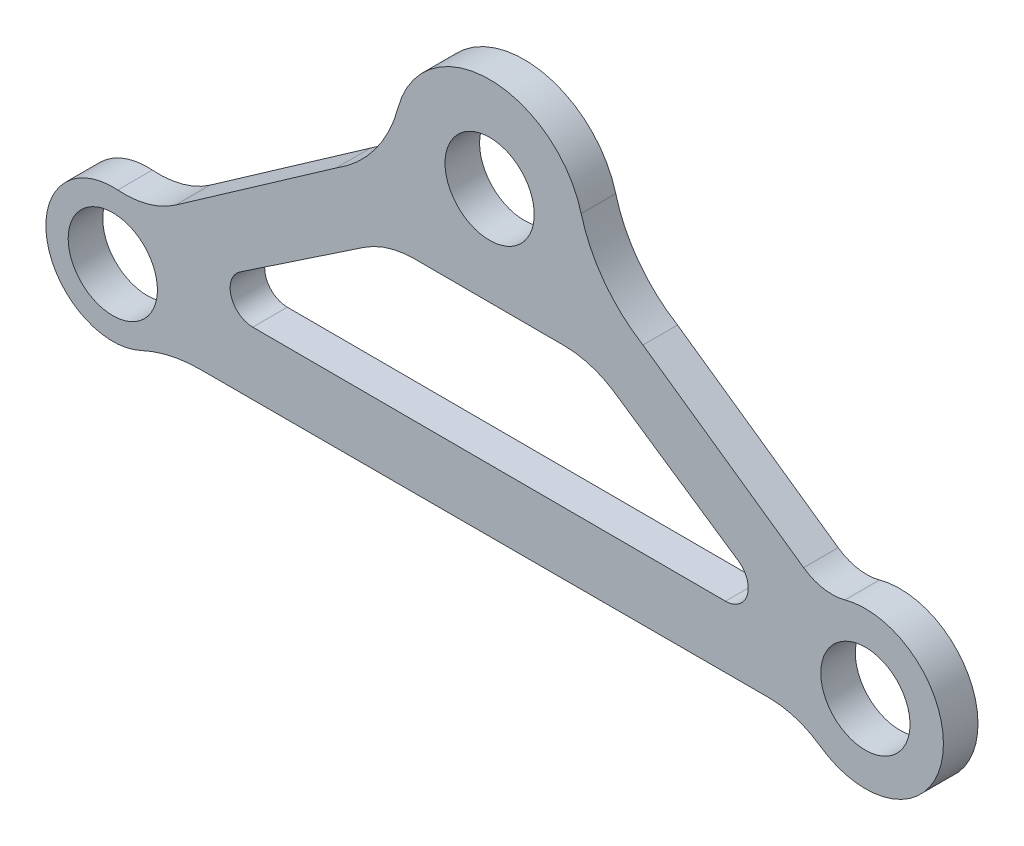
SolidWorks part; units mm, degrees
ref_plane "Front Plane" through (0, 0, 0) normal (0, 0, 1) x (1, 0, 0)
ref_plane "Top Plane" through (0, 0, 0) normal (0, 1, 0) x (1, 0, 0)
ref_plane "Right Plane" through (0, 0, 0) normal (1, 0, 0) x (0, 0, -1)
sketch "Sketch1" plane through (0, 0, 0) normal (0, 0, 1) x (1, 0, 0)
  line L0 (13.3736, -17.6685) -> (-13.446, -17.6134)
  line L1 (-22.5576, -20.3787) -> (-44.7444, -35.2777)
  line L2 (-42.4832, -42.7284) -> (42.3075, -42.9023)
  line L3 (44.5992, -35.461) -> (22.4738, -20.4711)
  line L4 (56.3265, -30.6845) -> (27.5, -10.5)
  line L6 (-27.5, -10.5) -> (-56.3265, -30.6845)
  line L8 (-51.8851, -54) -> (50.0933, -54)
  line L11 (-67.5934, -45.5) -> (67.4066, -45.5) construction
  circle A0 centre (67.4066, -45.5) radius 8
  circle A1 centre (0, 0) radius 8
  circle A2 centre (-67.5934, -45.5) radius 8
  arc A3 (-13.446, -17.6134) -> (-22.5576, -20.3787) centre (-13.4794, -33.8974) ccw
  arc A4 (-44.7444, -35.2777) -> (-42.4832, -42.7284) centre (-42.4748, -38.6574) ccw
  arc A5 (42.3075, -42.9023) -> (44.5992, -35.461) centre (42.3159, -38.8314) ccw
  arc A6 (22.4738, -20.4711) -> (13.3736, -17.6685) centre (13.3402, -33.9525) ccw
  arc A7 (59.327, -56.9333) -> (63.7525, -31.9853) centre (67.4066, -45.5) ccw
  arc A8 (56.3265, -30.6845) -> (63.7525, -31.9853) centre (61.4301, -23.3958) ccw
  arc A10 (16.4283, 4.3717) -> (-16.4283, 4.3717) centre (0, 0) ccw
  arc A12 (-66.6978, -33.5335) -> (-56.3265, -30.6845) centre (-65.5037, -17.5781) ccw
  arc A13 (-66.6978, -33.5335) -> (-62.4988, -56.3649) centre (-67.5934, -45.5) ccw
  arc A16 (59.327, -56.9333) -> (50.0933, -54) centre (50.0933, -70) ccw
  arc A17 (-16.4283, 4.3717) -> (-27.5, -10.5) centre (-40.5875, 10.8006) cw
  arc A18 (16.4283, 4.3717) -> (27.5, -10.5) centre (40.5875, 10.8006) ccw
  arc A19 (-62.4988, -56.3649) -> (-51.8851, -54) centre (-51.8851, -79) cw
  dimension "D2" = 67.5934
  dimension "D3" = 16
  dimension "D4" = 45.5
  dimension "D1" = 135
  dimension "D5" = 17
  dimension "D6" = 14
  dimension "D7" = 12
  dimension "D11" = 25
  dimension "D14" = 16
  dimension "D15" = 25
  dimension "D16" = 16
  dimension "D8" = 8.5
  dimension "D9" = 35
  dimension "D10" = 35
  dimension "D12" = 27.5
  dimension "D13" = 10.5
extrude "Boss-Extrude5" add sketch "Sketch1" along normal blind 6.2
